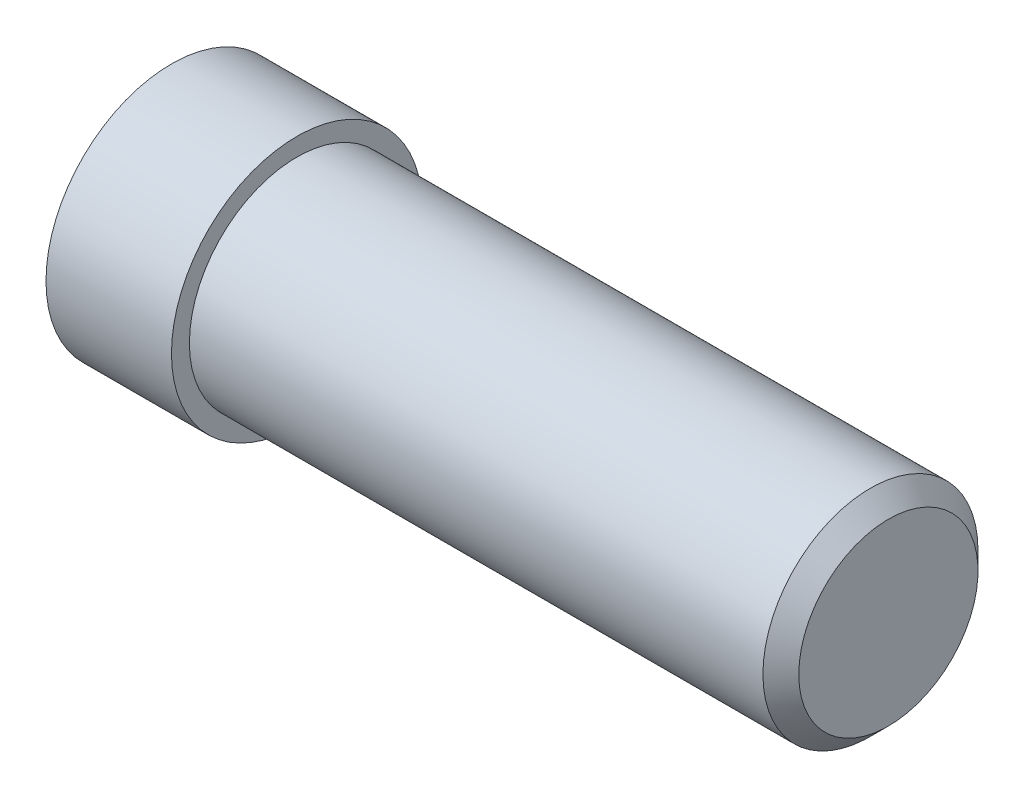
SolidWorks part; units mm, degrees
ref_plane "Front Plane" through (0, 0, 0) normal (0, 0, 1) x (1, 0, 0)
ref_plane "Top Plane" through (0, 0, 0) normal (0, 1, 0) x (1, 0, 0)
ref_plane "Right Plane" through (0, 0, 0) normal (1, 0, 0) x (0, 0, -1)
sketch "Sketch1" plane through (0, 0, 0) normal (0, 0, 1) x (1, 0, 0)
  line L0 (-48.8814, 20.1102) -> (32.6271, 20.1102) construction
  line L2 (-41.0508, 26.1102) -> (-8.0508, 26.1102)
  line L4 (-41.0508, 20.1102) -> (-8.0508, 20.1102)
  line L5 (-8.0508, 26.1102) -> (-8.0508, 20.1102)
  line L6 (-48.0508, 27.1102) -> (-41.0508, 27.1102)
  line L7 (-48.0508, 27.1102) -> (-48.0508, 20.1102)
  line L8 (-48.0508, 20.1102) -> (-41.0508, 20.1102)
  line L9 (-41.0508, 27.1102) -> (-41.0508, 26.1102)
  dimension "D1" = 7
  dimension "D2" = 7
  dimension "D3" = 33
  dimension "D4" = 6
revolve "Revolve1" add sketch "Sketch1" angle 360 about L0
chamfer "Chamfer1" distance 1 angle 45 1 edges at (-8.0508, 20.1102, 6)
scale "Scale1" scale about centroid uniform scaling yes scale factor 0.828947
